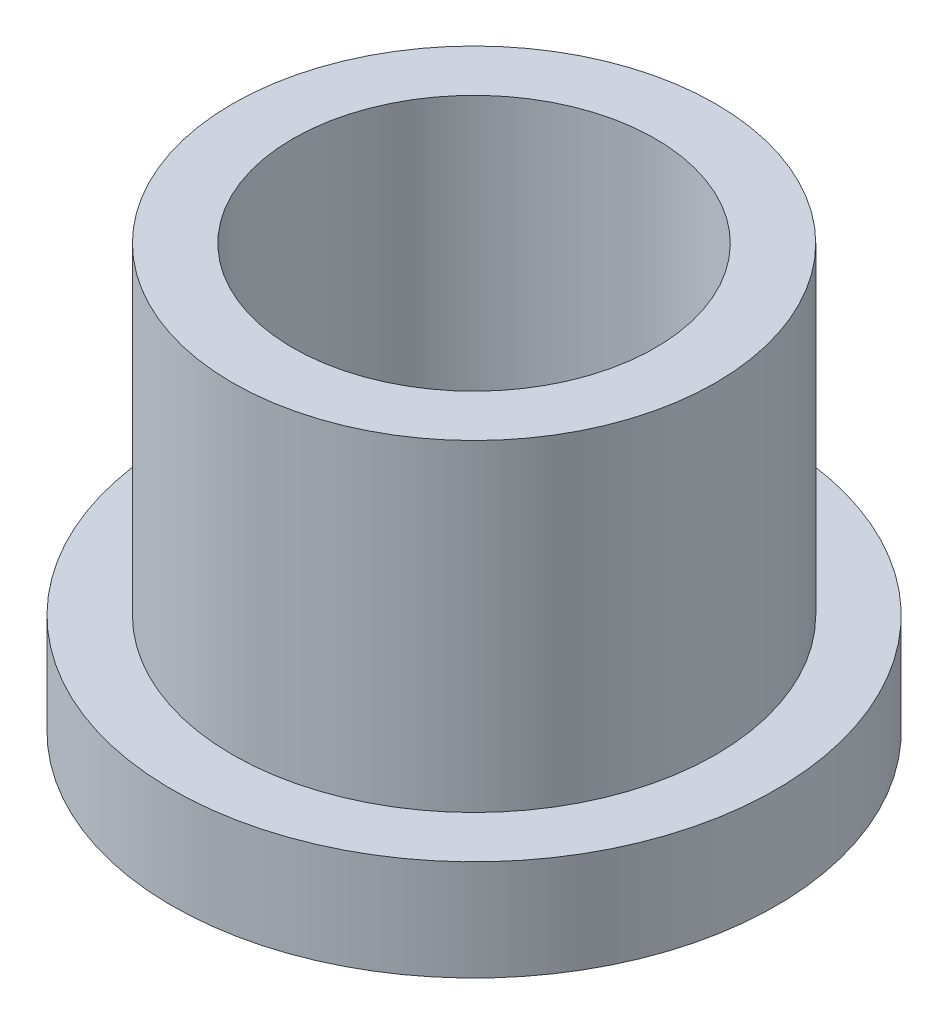
SolidWorks part; units mm, degrees
material "1.1191 (C45E)"
ref_plane "Alzado" through (0, 0, 0) normal (0, 0, 1) x (1, 0, 0)
ref_plane "Planta" through (0, 0, 0) normal (0, 1, 0) x (1, 0, 0)
ref_plane "Vista lateral" through (0, 0, 0) normal (1, 0, 0) x (0, 0, -1)
sketch "Croquis1" plane through (0, 0, 0) normal (0, 0, 1) x (1, 0, 0)
  line L0 (0, 0) -> (0, 5)
  line L1 (0, 5) -> (3, 5)
  line L2 (3, 5) -> (3, 21)
  line L3 (3, 21) -> (15, 21)
  line L5 (15, 0) -> (0, 0)
  line L6 (15, 21) -> (15, 0) construction
  line L7 (15, 21) -> (15, 0)
  dimension "D1" = 15
  dimension "D2" = 12
  dimension "D3" = 16
  dimension "D4" = 5
revolve "Revolución1" add sketch "Croquis1" angle 360 about L6
sketch "Croquis2" plane through (0, 21, 0) normal (0, 1, 0) x (1, 0, 0)
  circle A0 centre (15, 0) radius 9
  circle A1 centre (15, 0) radius 12 construction
  dimension "D1" = 3
extrude "Cortar-Extruir1" cut sketch "Croquis2" against normal through all both
